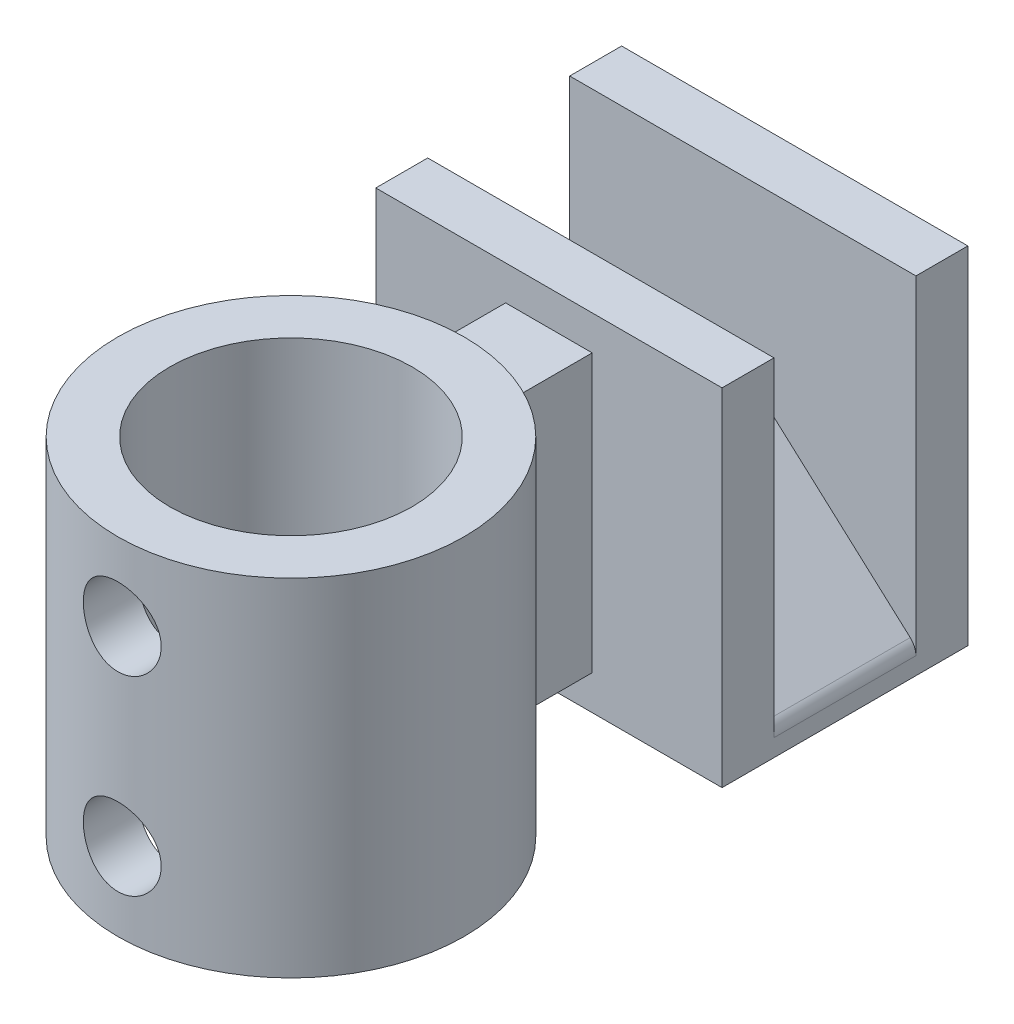
SolidWorks part; units mm, degrees
material "ABS"
ref_plane "Front Plane" through (0, 0, 0) normal (0, 0, 1) x (1, 0, 0)
ref_plane "Top Plane" through (0, 0, 0) normal (0, 1, 0) x (1, 0, 0)
ref_plane "Right Plane" through (0, 0, 0) normal (1, 0, 0) x (0, 0, -1)
sketch "Sketch2" plane through (0, 0, 0) normal (0, 0, 1) x (1, 0, 0)
  line L1 (-10, -5) -> (10, -5)
  line L2 (-10, -5) -> (-10, 5)
  line L3 (-10, 5) -> (10, 5)
  line L4 (10, -5) -> (10, 5)
  line L5 (-10, -5) -> (10, 5) construction
  line L6 (-10, 5) -> (10, -5) construction
  point P0 (0, 0)
  dimension "D1" = 10
  dimension "D2" = 20
extrude "Boss-Extrude1" add sketch "Sketch2" along normal mid plane 8.2
chamfer "Chamfer1" distance 9.5 angle 42 2 edges at (10, 5, 0) (-10, 5, 0)
fillet "Fillet3" radius 1 4 edges at (-10, -3.5538, 0) (10, -3.5538, 0) (0.5, 5, 0) (-0.5, 5, 0)
sketch "Sketch3" plane through (0, 0, 4.1) normal (0, 0, 1) x (1, 0, 0)
  line L0 (-10, -5) -> (10, -5) construction
  line L1 (-10, 15) -> (10, 15)
  line L2 (-10, 15) -> (-10, -5)
  line L3 (-10, -5) -> (10, -5)
  line L4 (10, 15) -> (10, -5)
  line L5 (-10, 15) -> (10, -5) construction
  line L6 (-10, -5) -> (10, 15) construction
  point P0 (0, 5)
  dimension "D1" = 20
  dimension "D2" = 20
extrude "Boss-Extrude2" add sketch "Sketch3" along normal blind 3
mirror "Mirror1" about plane through (0, 0, 0) normal (0, 0, 1) of "Boss-Extrude2"
sketch "Sketch6" plane through (0, 0, 0) normal (0, 1, 0) x (1, 0, 0)
  circle A0 centre (0, -22) radius 10
  circle A1 centre (0, -22) radius 7
  dimension "D1" = 14
  dimension "D2" = 3
  dimension "D3" = 22
extrude "Boss-Extrude3" add sketch "Sketch6" along normal up to surface and the other way up to surface separate body up to face at (0, 15, 5.6) other way up to face at (0, -5, 0)
sketch "Sketch5" plane through (0, 0, 7.1) normal (0, 0, 1) x (1, 0, 0)
  line L0 (-10, -5) -> (10, -5) construction
  line L1 (-2.5, 13) -> (2.5, 13)
  line L2 (-2.5, 13) -> (-2.5, -3)
  line L3 (-2.5, -3) -> (2.5, -3)
  line L4 (2.5, 13) -> (2.5, -3)
  line L5 (-2.5, 13) -> (2.5, -3) construction
  line L6 (-2.5, -3) -> (2.5, 13) construction
  line L7 (10, 15) -> (-10, 15) construction
  point P0 (0, 5)
  dimension "D1" = 2
  dimension "D2" = 2
  dimension "D3" = 5
extrude "Boss-Extrude4" add sketch "Sketch5" along normal up to surface (8.3617 mm away)
ref_plane "Plane1" through (0, 0, 20) normal (0, 0, 1) x (1, 0, 0)
sketch "Sketch7" plane through (0, 0, 20) normal (0, 0, 1) x (1, 0, 0)
  line L2 (-10, -5) -> (10, -5) construction
  line L3 (7, 15) -> (-7, 15) construction
  circle A0 centre (0, 10.5) radius 2.25
  circle A1 centre (0, -0.5) radius 2.25
  dimension "D1" = 4.5
  dimension "D2" = 4.5
  dimension "D3" = 4.5
  dimension "D4" = 4.5
extrude "Cut-Extrude1" cut sketch "Sketch7" along normal up to surface (11.7436 mm away)
equation "\"BEAM_WIDTH\" = 8.2mm"
equation "\"D1@Boss-Extrude1\"=\"BEAM_WIDTH\""
